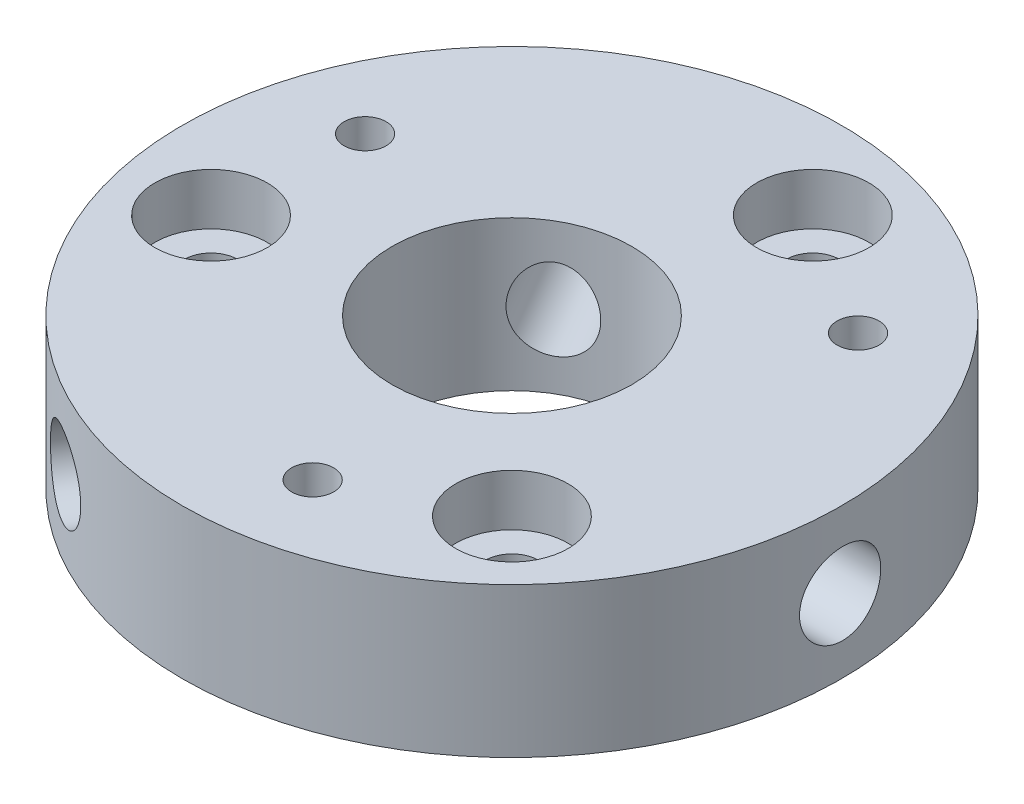
SolidWorks part; units mm, degrees
ref_plane "Front Plane" through (0, 0, 0) normal (0, 0, 1) x (1, 0, 0)
ref_plane "Top Plane" through (0, 0, 0) normal (0, 1, 0) x (1, 0, 0)
ref_plane "Right Plane" through (0, 0, 0) normal (1, 0, 0) x (0, 0, -1)
sketch "Sketch1" plane through (0, 0, 0) normal (0, 1, 0) x (1, 0, 0)
  circle A0 centre (0, 0) radius 13.97
  dimension "D1" = 27.94
extrude "Boss-Extrude1" add sketch "Sketch1" along normal blind 6.35
hole_wizard "CBORE for #2 Socket Head Cap Screw1" positions "Sketch3" profile "Sketch4" counterbore size "#2" standard "ANSI Inch" end condition through all
sketch "Sketch3" plane through (0, 6.35, 0) normal (0, 1, 0) x (1, 0, 0)
  line L3 (0, 0) -> (7.3638, -7.3638)
  point P0 (7.3638, -7.3638)
sketch "Sketch4" plane through (7.3638, 6.35, 7.3638) normal (1, 0, 0) x (0, 0, 1)
  line L0 (0, 0) -> (0, 6.35)
  line L1 (0, 6.35) -> (1.1303, 6.35)
  line L3 (1.1303, 6.35) -> (1.1303, 2.1844)
  line L4 (1.1303, 2.1844) -> (2.3812, 2.1844)
  line L5 (2.3812, 2.1844) -> (2.3812, 0)
  line L7 (2.3812, 0) -> (0, 0)
  line L11 (0, -6.35) -> (0, 107.95) construction
  dimension "Thru Hole Dia." = 2.2606
  dimension "Thru Hole Depth" = 6.35
  dimension "C'Bore Dia." = 4.7625
  dimension "C'Bore Depth" = 2.1844
pattern_circular "CirPattern1" count 3 over 360 about axis through (0, 0, 0) along (0, 1, 0) of "CBORE for #2 Socket Head Cap Screw1"
sketch "Sketch9" plane through (0, 6.35, 0) normal (0, 1, 0) x (1, 0, 0)
  line L0 (0, 0) -> (7.9776, 6.694)
  circle A0 centre (7.9776, 6.694) radius 1.4122
hole_wizard "Tap Drill for #2-56 Tap2" positions "3DSketch1" profile "Sketch10" hole size "#2-56" standard "ANSI Inch"
sketch3d "3DSketch1"
  point P0 (7.9776, 6.35, -6.694)
sketch "Sketch10" plane through (7.9776, 6.35, -6.694) normal (1, 0, 0) x (0, 0, 1)
  line L0 (0, 0) -> (0, 4.5982)
  line L1 (0, 4.5982) -> (0.889, 4.064)
  line L2 (0.889, 4.064) -> (0.889, 0)
  line L5 (0.889, 0) -> (0, 0)
  line L10 (0, 4.5982) -> (-0.889, 4.064) construction
  line L11 (0, -6.35) -> (0, 107.95) construction
  dimension "Hole Dia." = 1.778
  dimension "Hole Depth" = 4.064
  dimension "Drill Angle" = 118
pattern_circular "CirPattern2" count 3 every 120 about axis through (0, 0, 0) along (0, 1, 0) of "Tap Drill for #2-56 Tap2"
ref_plane "Plane1" [suppressed] through (0, 3.175, 0) normal (0, 1, 0) x (1, 0, 0)
sketch "Sketch11" [suppressed] plane through (0, 3.175, 0) normal (0, 1, 0) x (1, 0, 0)
  line L0 (0, 0) -> (-7.135, -12.0105)
  circle A0 centre (0, 0) radius 13.97 construction
ref_plane "Plane2" [suppressed] through (-7.135, 3.175, 12.0105) normal (-0.5107, 0, 0.8597) x (0.8597, 0, 0.5107)
hole_wizard "Tap Drill for #8-32 Tap2" positions "3DSketch3" profile "Sketch15" hole size "#8-32" standard "ANSI Inch"
sketch3d "3DSketch3"
  point P0 (-6.9425, 3.1056, 12.1228)
sketch "Sketch15" plane through (-6.9425, 3.1056, 12.1228) normal (0, 1, 0) x (0.8678, 0, 0.497)
  line L0 (0, 0) -> (0, 10.3393)
  line L1 (0, 10.3393) -> (1.7272, 8.89)
  line L2 (1.7272, 8.89) -> (1.7272, 0)
  line L5 (1.7272, 0) -> (0, 0)
  line L10 (0, 10.3393) -> (-1.7272, 8.89) construction
  line L11 (0, -6.35) -> (0, 107.95) construction
  dimension "Hole Dia." = 3.4544
  dimension "Hole Depth" = 8.89
  dimension "Drill Angle" = 100
pattern_circular "CirPattern3" count 3 every 120 about axis through (0, 6.35, 0) along (0, -1, 0) of "Tap Drill for #8-32 Tap2"
sketch "Sketch16" plane through (0, 6.35, 0) normal (0, 1, 0) x (1, 0, 0)
  circle A0 centre (0, 0) radius 5.08
extrude "Cut-Extrude2" cut sketch "Sketch16" against normal up to next contours A0
